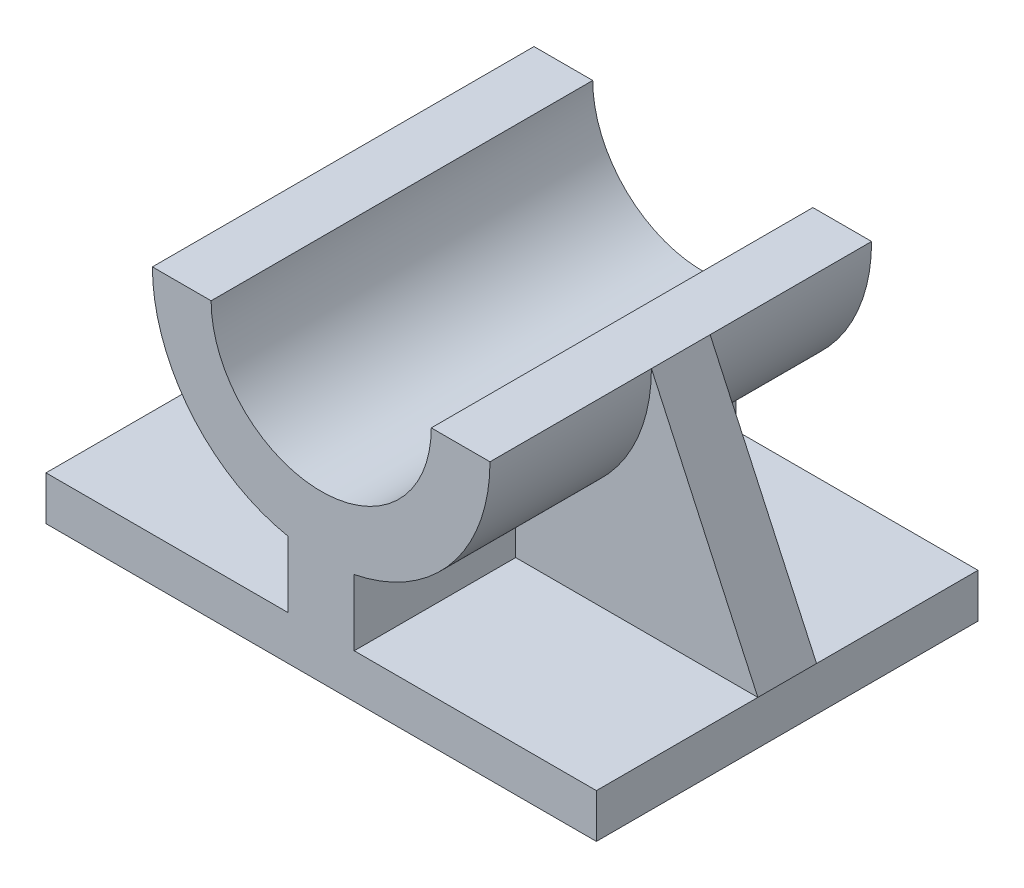
SolidWorks part; units mm, degrees
ref_plane "Front Plane" through (0, 0, 0) normal (0, 0, 1) x (1, 0, 0)
ref_plane "Top Plane" through (0, 0, 0) normal (0, 1, 0) x (1, 0, 0)
ref_plane "Right Plane" through (0, 0, 0) normal (1, 0, 0) x (0, 0, -1)
sketch "Sketch1" plane through (0, 0, 0) normal (0, 0, 1) x (1, 0, 0)
  line L0 (37.5, -37.5555) -> (-37.5, -37.5555)
  line L1 (-37.5, -37.5555) -> (-37.5, -31.5555)
  line L2 (-37.5, -31.5555) -> (-4.5, -31.5555)
  line L3 (37.5, -37.5555) -> (37.5, -31.5555)
  line L4 (37.5, -31.5555) -> (4.5, -31.5555)
  line L5 (0, 0) -> (0, -37.5555) construction
  line L6 (-4.5, -31.5555) -> (-4.5, -22.5555)
  line L7 (4.5, -31.5555) -> (4.5, -22.5555)
  line L8 (-23, 0) -> (23, 0)
  arc A0 (-15, 0) -> (15, 0) centre (0, 0) ccw
  arc A1 (-23, 0) -> (-4.5, -22.5555) centre (0, 0) ccw
  arc A2 (4.5, -22.5555) -> (23, 0) centre (0, 0) ccw
  point P7 (0, -37.5555)
  dimension "D1" = 30
  dimension "D2" = 46
  dimension "D3" = 75
  dimension "D4" = 6
  dimension "D5" = 33
  dimension "D6" = 33
  dimension "D7" = 9
extrude "Boss-Extrude1" add sketch "Sketch1" against normal mid plane 52 contours L5 A0 L8 A1 L6 L2 L1 L0 | A0 L5 L0 L3 L4 L7 A2 L8
ref_plane "Plane2" through (23, 0, 26) normal (0, 0, 1) x (1, 0, 0)
sketch "Sketch2" plane through (0, 0, 0) normal (0, 0, 1) x (1, 0, 0)
  line L0 (23, 0) -> (37.5, -31.5555)
rib "Rib1" sketch "Sketch2" sketch "Sketch2" thickness 8 extrusion direction parallel to sketch draft on no parameters "D1"=8
mirror "Mirror1" about plane through (0, 0, 0) normal (1, 0, 0) of "Rib1"
